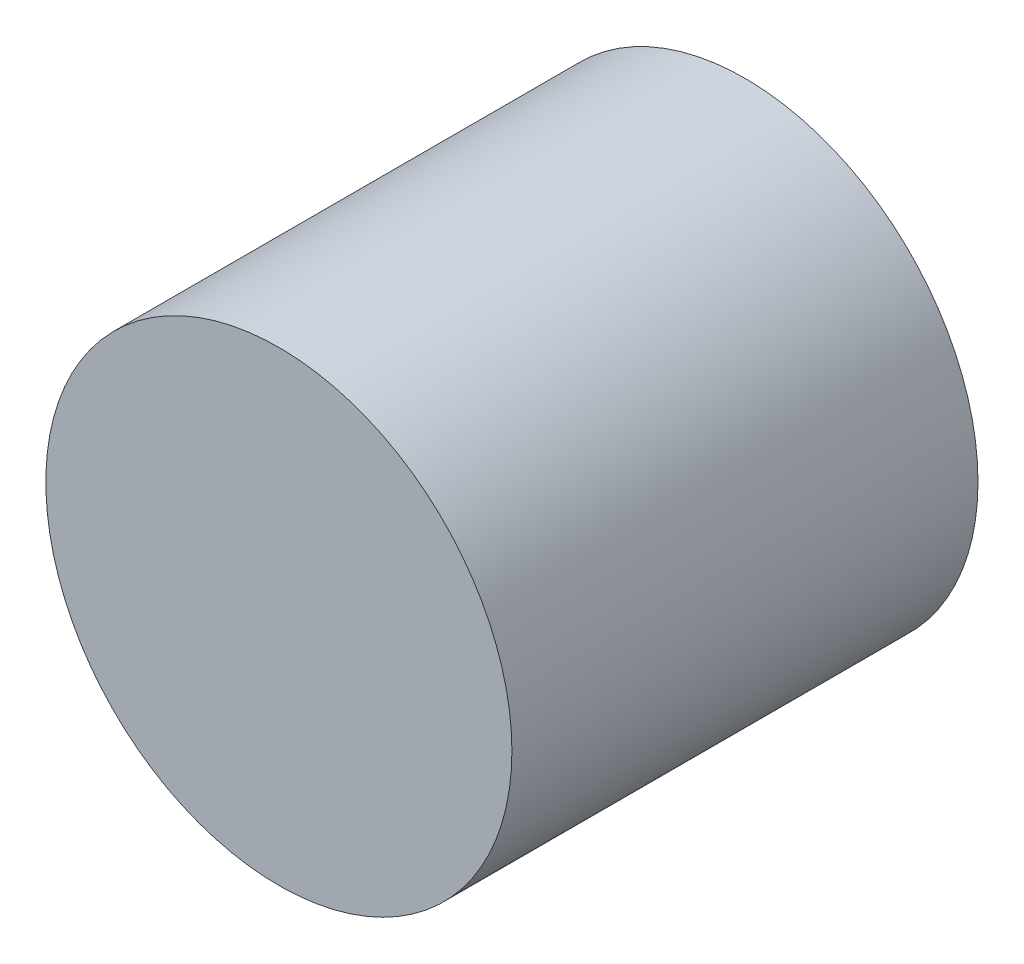
SolidWorks part; units mm, degrees
ref_plane "Спереди" through (0, 0, 0) normal (0, 0, 1) x (1, 0, 0)
ref_plane "Сверху" through (0, 0, 0) normal (0, 1, 0) x (1, 0, 0)
ref_plane "Справа" through (0, 0, 0) normal (1, 0, 0) x (0, 0, -1)
other "Configuration Table"
sketch "Проход_ровно6" plane through (0, 0, 0) normal (0, 0, 1) x (1, 0, 0)
  circle A0 centre (0, 0) radius 3
extrude "Цилиндр_6" add sketch "Проход_ровно6" along normal blind 6
equation "\"D1@Цилиндр_6\" = \"Толщина тонких панелей\""
equation "\"Фанера\"=6"
equation "\"Ширина шипа\"=16"
equation "\"Межосевое шипов\"=40"
equation "\"Посадочный зазор\"=0.15"
equation "\"Основная фреза\"=6"
equation "\"Мелкая фреза\"=6"
equation "\"Запас разгрузки\"=0.05"
equation "\"Ширина образца\"=84"
equation "\"Высота образца\"=50"
equation "\"Канал М6\"=6"
equation "\"Гайка под ключ\"=10.3"
equation "\"Длина кармана гайки\"=6.2"
equation "\"Отступ гайки\"=12"
equation "\"Диаметр1@Проход_ровно6\" = \"Канал М6\""
equation "\"Ширина груза\"= 420"
equation "\"Глубина груза\"= 490"
equation "\"Высота груза\"= 297"
equation "\"Ширина ячейки\"= \"Ширина груза\" + 10"
equation "\"Глубина ячейки\"= \"Глубина груза\" + 10"
equation "\"Высота ячейки\"= \"Высота груза\" + 10 + 13"
equation "\"Колво ячеек ширина\"= 2"
equation "\"Колво ячеек высота\"= 2"
equation "\"Толщина стенки\" = \"Толщина тонких панелей\""
equation "\"Крепление дверцы\"= 5 "
equation "\"Ширина рейки\"= \"Толщина шестерни\""
equation "\"Высота рейки\"= 20"
equation "\"Высота пола\" = 2*\"Толщина тонких панелей\""
equation "\"Колво полозьев\"= 5"
equation "\"Отступ рейки\"= 20"
equation "\"Глубина каретки\"= \"Глубина ячейки\" + 30 + \"Мотор Y высота корпуса\" + 20"
equation "\"Длинна рейки\" = (\"Ширина ячейки\"+\"Толщина вертикальных стенок\"+\"Крепление дверцы\")*\"Колво ячеек ширина\"+\"Ширина ячейки выгрузки\"*\"Колво выгрузки\"+\"Толщина вертикальных стенок\"+2*\"Отступ крепления мотора фиксации\"-\"Крепление дверцы\"*\"Колво ячеек ширина\""
equation "\"Отступ шпильки\"= 26"
equation "\"Диаметр шпильки\"= 5"
equation "\"Длинна шпильки\" = (\"Высота ячейки\"+\"Толщина горизонтальных плит\"+\"Высота пола\")*\"Колво ячеек высота\"+2*(\"Толщина горизонтальных плит\"+\"Отступ рейки\")"
equation "\"Ширина пластины\"= 50  "
equation "\"Высота зона выгрузки\"= \"Высота ячейки\" * 2 + \"Толщина стенки\" * 2"
equation "\"Колво выгрузки\"= 1"
equation "\"Ширина ячейки выгрузки\" = \"Ширина ячейки\"+\"Толщина вертикальных стенок\"+2*\"Отступ крепления мотора фиксации\""
equation "\"Отступ крепления мотора фиксации\" = (\"Ширина пластины\"+20-\"Толщина вертикальных стенок\")/2"
equation "\"Мотор X ширина корпуса\"= 42.3"
equation "\"Мотор X высота корпуса\"= 42.3"
equation "\"Мотор X длина корпуса\"= 40"
equation "\"Мотор X вылет вала\"= 19.8"
equation "\"Мотор Y ширина корпуса\"= 42.3"
equation "\"Мотор Y высота корпуса\"= 42.3"
equation "\"Мотор Y длина корпуса\"= 48"
equation "\"Мотор Y вылет вала\"= 30"
equation "\"Мотор Z ширина корпуса\"= 42"
equation "\"Мотор Z высота корпуса\"= 42"
equation "\"Мотор Z длина корпуса\"= 40"
equation "\"Мотор Z вылет вала\"= 23"
equation "\"Мотор диаметр вала ПРЕДВ\"= 5"
equation "\"Мотор шаг крепления ПРЕДВ\"= 31"
equation "\"Мотор диаметр отверстий ПРЕДВ\"= 3"
equation "\"Мотор глубина отверстий ПРЕДВ\"= 4.5"
equation "\"Мотор диаметр буртика ПРЕДВ\"= 22"
equation "\"Мотор высота буртика ПРЕДВ\"= 2"
equation "\"Мотор диаметр шкива ПРЕДВ\"= 16"
equation "\"Мотор длина шкива ПРЕДВ\"= 12"
equation "\"Мотор отступ шкива ПРЕДВ\"= 5"
equation "\"Мотор X шаг градусов\"= 1.8"
equation "\"Мотор Y шаг градусов\"= 1.8"
equation "\"Мотор Z шаг градусов\"= 1.8"
equation "\"Мотор Y диаметр ротора\"= 25.78"
equation "\"Толщина шестерни\"= 10"
equation "\"Толщина тонких панелей\"= 6"
equation "\"Толщина вертикальных стенок\"= 18"
equation "\"Толщина горизонтальных плит\"= 18"
equation "\"Базовая высота корпуса\"= (\"Высота ячейки\"+\"Толщина тонких панелей\"+\"Высота пола\")*\"Колво ячеек высота\"+6*\"Толщина тонких панелей\"+\"Мотор X ширина корпуса\"+\"Мотор Y ширина корпуса\"+75"
equation "\"Высота корпуса\"= (\"Высота ячейки\"+\"Толщина горизонтальных плит\"+\"Высота пола\")*\"Колво ячеек высота\"+2*\"Толщина горизонтальных плит\"+4*\"Толщина тонких панелей\"+\"Мотор X ширина корпуса\"+\"Мотор Y ширина корпуса\"+75"
equation "\"Смещение центра корпуса\"= (\"Высота корпуса\"-\"Базовая высота корпуса\")/2-(\"Толщина горизонтальных плит\"-\"Толщина тонких панелей\")"
equation "\"Отметка пола\"= -\"Базовая высота корпуса\"/2+\"Толщина тонких панелей\""
equation "\"Отметка потолка\"= \"Отметка пола\"+\"Высота корпуса\"-2*\"Толщина горизонтальных плит\""
equation "\"Отметка верхней полки\"= \"Отметка потолка\"-(28+\"Толщина тонких панелей\")-\"Высота ячейки\"-\"Высота пола\""
equation "\"Отметка нижней полки\"= \"Отметка верхней полки\"-\"Высота ячейки\"-\"Высота пола\"-\"Толщина горизонтальных плит\""
